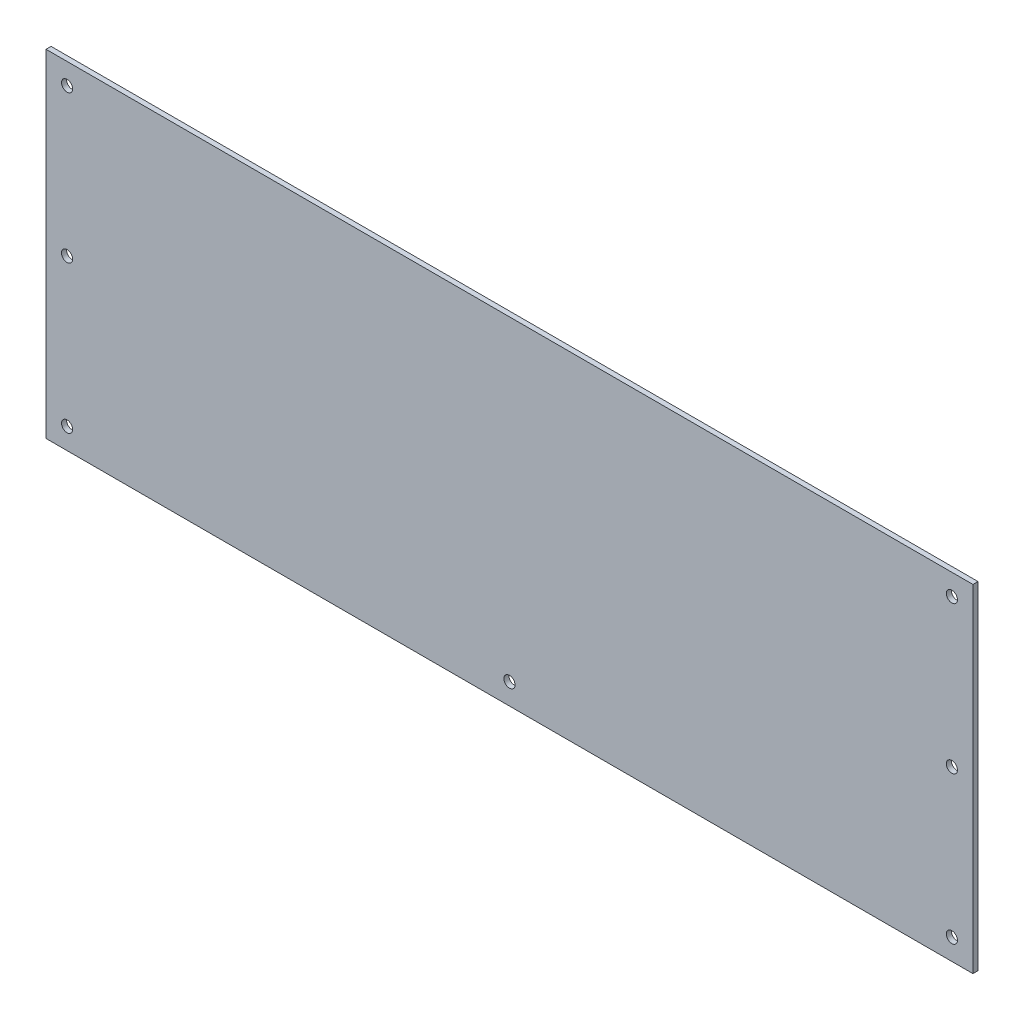
SolidWorks part; units mm, degrees
material "Acrylic (Medium-high impact)"
ref_plane "Front Plane" through (0, 0, 0) normal (0, 0, 1) x (1, 0, 0)
ref_plane "Top Plane" through (0, 0, 0) normal (0, 1, 0) x (1, 0, 0)
ref_plane "Right Plane" through (0, 0, 0) normal (1, 0, 0) x (0, 0, -1)
sketch "Sketch1" plane through (0, 0, 0) normal (0, 0, 1) x (1, 0, 0)
  line L1 (0, 0) -> (550, 0)
  line L2 (0, 0) -> (0, 200)
  line L3 (0, 200) -> (550, 200)
  line L4 (550, 0) -> (550, 200)
  dimension "D1" = 550
  dimension "D2" = 200
extrude "Boss-Extrude1" add sketch "Sketch1" along normal blind 3
hole_wizard "M6 Clearance Hole1" positions "Sketch2" profile "Sketch3" hole size "M6" standard "ANSI Metric" end condition through all
sketch "Sketch2" plane through (0, 0, 3) normal (0, 0, 1) x (1, 0, 0)
  line L1 (550, 200) -> (0, 200) construction
  line L2 (0, 200) -> (0, 0) construction
  line L3 (0, 0) -> (550, 0) construction
  line L4 (550, 0) -> (550, 200) construction
  point P0 (12.5, 100)
  point P2 (12.5, 187.5)
  point P4 (12.5, 12.5)
  point P6 (275, 12.5)
  point P10 (537.5, 12.5)
  point P12 (537.5, 100)
  point P14 (537.5, 187.5)
  point P40 (0, 100)
  point P42 (275, 0)
  dimension "D1" = 12.5
  dimension "D2" = 12.5
  dimension "D3" = 12.5
  dimension "D4" = 12.5
sketch "Sketch3" plane through (12.5, 100, 3) normal (1, 0, 0) x (0, -1, 0)
  line L0 (0, 0) -> (0, 3)
  line L1 (0, 3) -> (3.3, 3)
  line L2 (3.3, 3) -> (3.3, 0)
  line L5 (3.3, 0) -> (0, 0)
  line L11 (0, -6.35) -> (0, 107.95) construction
  dimension "Thru Hole Dia." = 6.6
  dimension "Thru Hole Depth" = 3
